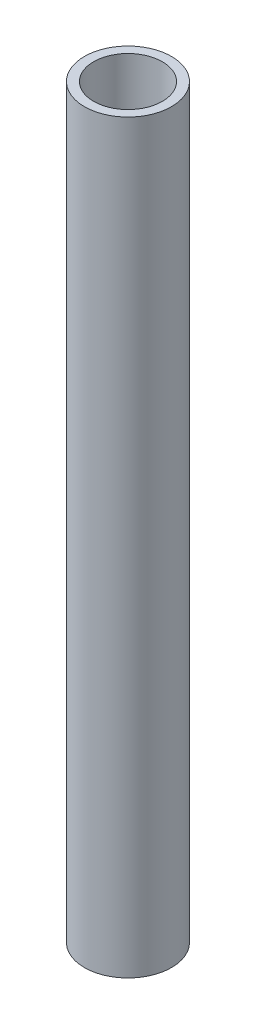
SolidWorks part; units mm, degrees
ref_plane "Front Plane" through (0, 0, 0) normal (0, 0, 1) x (1, 0, 0)
ref_plane "Top Plane" through (0, 0, 0) normal (0, 1, 0) x (1, 0, 0)
ref_plane "Right Plane" through (0, 0, 0) normal (1, 0, 0) x (0, 0, -1)
sketch "Sketch1" plane through (0, 0, 0) normal (0, 1, 0) x (1, 0, 0)
  circle A0 centre (0, 0) radius 24.13
  circle A1 centre (0, 0) radius 19.05
  dimension "D1" = 48.26
  dimension "D2" = 38.1
extrude "Boss-Extrude1" add sketch "Sketch1" along normal mid plane 413.258
